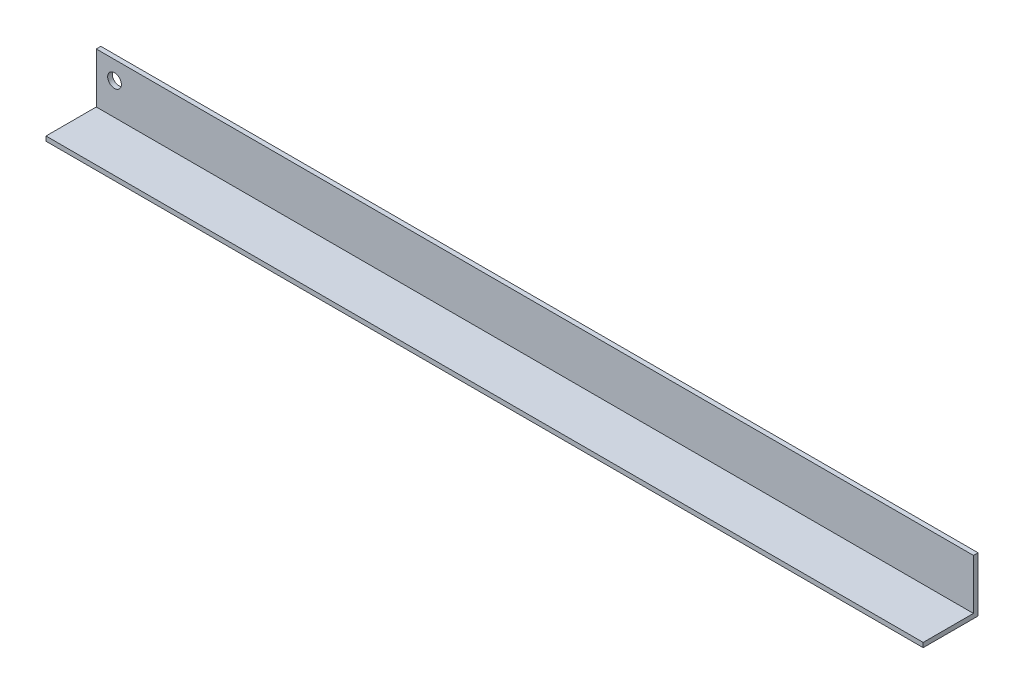
SolidWorks part; units mm, degrees
material "Plain Carbon Steel"
ref_plane "Front Plane" through (0, 0, 0) normal (0, 0, 1) x (1, 0, 0)
ref_plane "Top Plane" through (0, 0, 0) normal (0, 1, 0) x (1, 0, 0)
ref_plane "Right Plane" through (0, 0, 0) normal (1, 0, 0) x (0, 0, -1)
sketch "Sketch1" plane through (0, 0, 0) normal (1, 0, 0) x (0, 0, -1)
  line L0 (-38.1, 0) -> (0, 0)
  line L1 (55, 0) -> (-55, 0) construction
  line L2 (0, 0) -> (0, 38.1)
  line L3 (0, 55) -> (0, -55) construction
  dimension "D1" = 38.1
extrude "Extrude-Thin1" add sketch "Sketch1" along normal mid plane 609.6 thin thin type one direction reverse wall 3.175
sketch "Sketch2" plane through (0, 0, 0) normal (0, 0, -1) x (-1, 0, 0)
  line L1 (-304.8, 0) -> (-304.8, 38.1) construction
  line L2 (-304.8, 38.1) -> (304.8, 38.1) construction
  circle A1 centre (292.1, 25.4) radius 4.7625
  point P6 (0, 0)
  dimension "D1" = 596.9
  dimension "D3" = 9.525
  dimension "D2" = 12.7
extrude "Cut-Extrude1" cut sketch "Sketch2" against normal up to next
